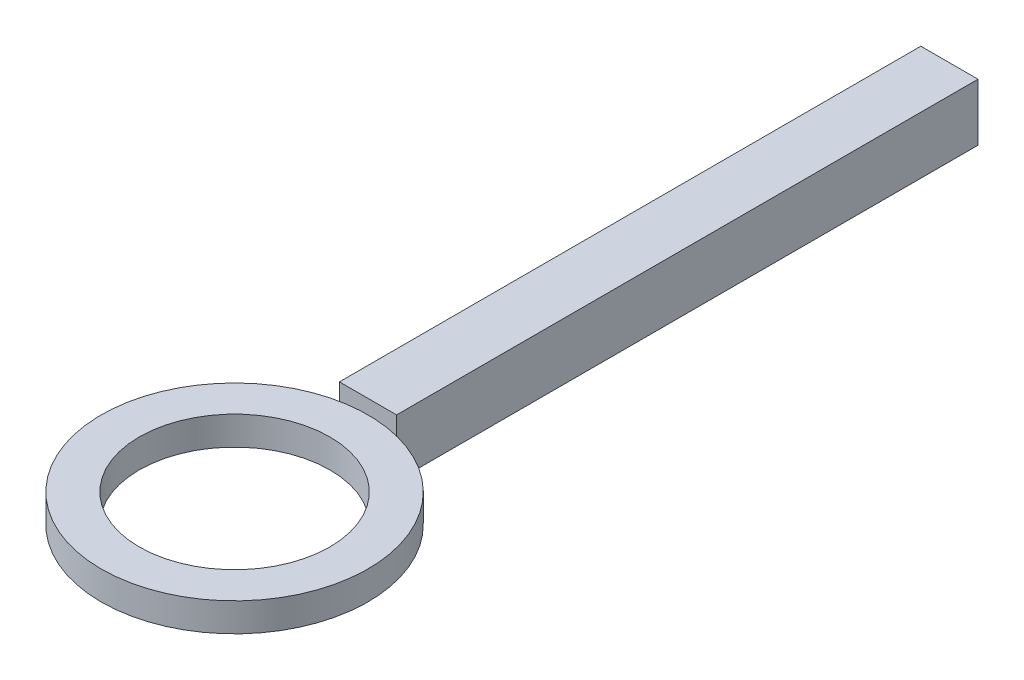
SolidWorks part; units mm, degrees
ref_plane "Front Plane" through (0, 0, 0) normal (0, 0, 1) x (1, 0, 0)
ref_plane "Top Plane" through (0, 0, 0) normal (0, 1, 0) x (1, 0, 0)
ref_plane "Right Plane" through (0, 0, 0) normal (1, 0, 0) x (0, 0, -1)
ref_plane "P_Top_m3" through (0, -3, 0) normal (0, 1, 0) x (1, 0, 0)
sketch "Sketch1" plane through (0, -3, 0) normal (0, 1, 0) x (1, 0, 0)
  circle A0 centre (0, -150) radius 28
  circle A1 centre (0, -150) radius 20
extrude "Ring" add sketch "Sketch1" along normal blind 6
ref_plane "P_Top_m6" through (0, -6, 0) normal (0, 1, 0) x (1, 0, 0)
sketch "Sketch2" plane through (0, -6, 0) normal (0, 1, 0) x (1, 0, 0)
  line L0 (-6, -122) -> (6, -122)
  line L1 (6, -122) -> (6, 0)
  line L2 (6, 0) -> (-6, 0)
  line L3 (-6, 0) -> (-6, -122)
extrude "Handle" add sketch "Sketch2" along normal blind 12
